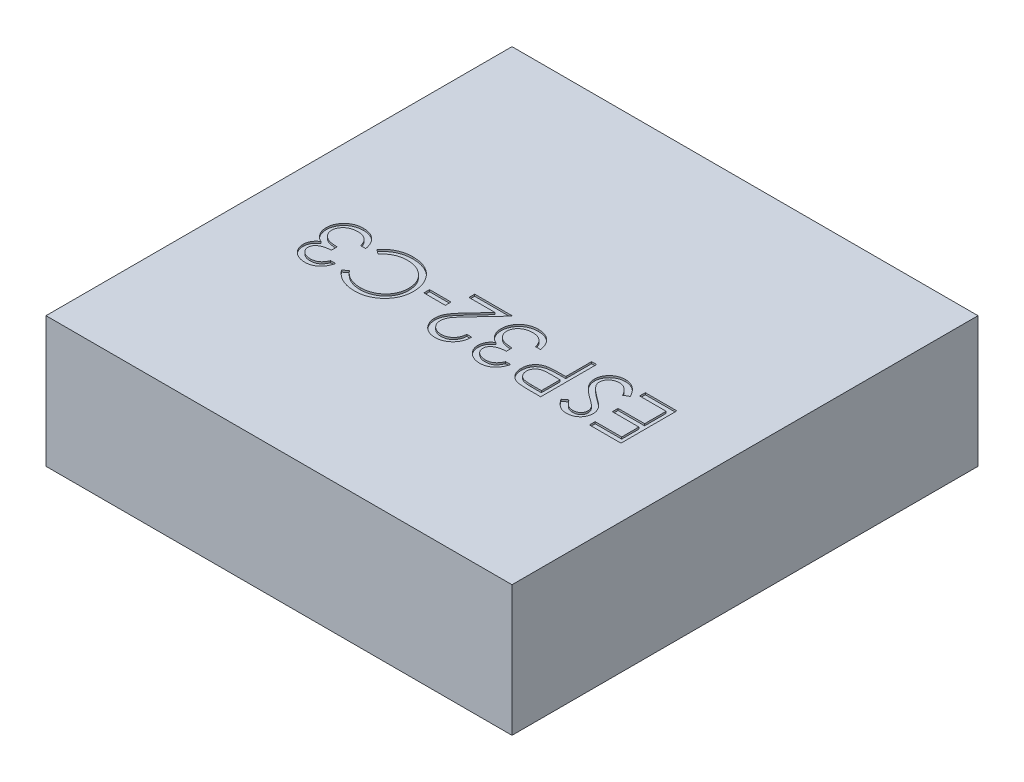
SolidWorks part; units mm, degrees
ref_plane "Front Plane" through (0, 0, 0) normal (0, 0, 1) x (1, 0, 0)
ref_plane "Top Plane" through (0, 0, 0) normal (0, 1, 0) x (1, 0, 0)
ref_plane "Right Plane" through (0, 0, 0) normal (1, 0, 0) x (0, 0, -1)
sketch "BaseS" plane through (0, 0, 0) normal (0, 1, 0) x (1, 0, 0)
  line L1 (-2.5, 2.5) -> (2.5, 2.5)
  line L2 (-2.5, 2.5) -> (-2.5, -2.5)
  line L3 (-2.5, -2.5) -> (2.5, -2.5)
  line L4 (2.5, 2.5) -> (2.5, -2.5)
  line L5 (-2.5, 2.5) -> (2.5, -2.5) construction
  line L6 (-2.5, -2.5) -> (2.5, 2.5) construction
  point P0 (0, 0)
  dimension "Dim" = 5
extrude "Base" add sketch "BaseS" along normal blind 1.4
sketch "PartNumberS" plane through (0, 1.4, 0) normal (0, 1, 0) x (1, 0, 0)
  line L0 (2.5, 0) -> (-2.5, 0) construction
  line L1 (2.5, -2.5) -> (2.5, 2.5) construction
  line L2 (-2.5, 2.5) -> (-2.5, -2.5) construction
  line L3 (-2.5, -2.5) -> (2.5, -2.5) construction
  text T0 "ESP32­C3" font "Century Gothic" height 0.6
  dimension "YDim" = 2.5
extrude "PartNumber" cut sketch "PartNumberS" against normal blind 0.02
